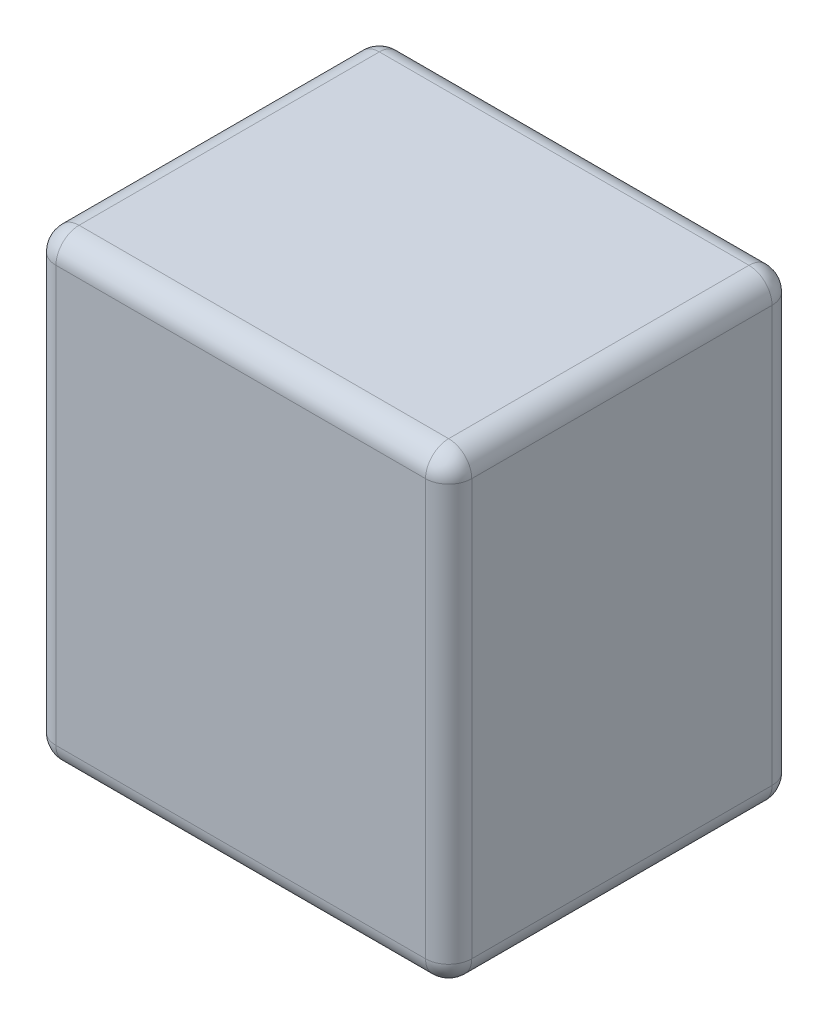
SolidWorks part; units mm, degrees
ref_plane "Front Plane" through (0, 0, 0) normal (0, 0, 1) x (1, 0, 0)
ref_plane "Top Plane" through (0, 0, 0) normal (0, 1, 0) x (1, 0, 0)
ref_plane "Right Plane" through (0, 0, 0) normal (1, 0, 0) x (0, 0, -1)
sketch "Sketch1" plane through (0, 0, 0) normal (0, 0, 1) x (1, 0, 0)
  line L1 (-22.86, 25.4) -> (22.86, 25.4)
  line L2 (-22.86, 25.4) -> (-22.86, -25.4)
  line L3 (-22.86, -25.4) -> (22.86, -25.4)
  line L4 (22.86, 25.4) -> (22.86, -25.4)
  line L5 (-22.86, 25.4) -> (22.86, -25.4) construction
  line L6 (-22.86, -25.4) -> (22.86, 25.4) construction
  point P0 (0, 0)
  dimension "D1" = 45.72
  dimension "D2" = 50.8
extrude "Boss-Extrude1" add sketch "Sketch1" along normal blind 38.1
fillet "Fillet1" radius 2.54 12 edges at (0, -25.4, 0) (22.86, -25.4, 19.05) (22.86, 0, 0) (22.86, 0, 38.1) (-22.86, 0, 38.1) (-22.86, -25.4, 19.05) (-22.86, 0, 0) (0, -25.4, 38.1) (0, 25.4, 38.1) (0, 25.4, 0) (22.86, 25.4, 19.05) (-22.86, 25.4, 19.05)
